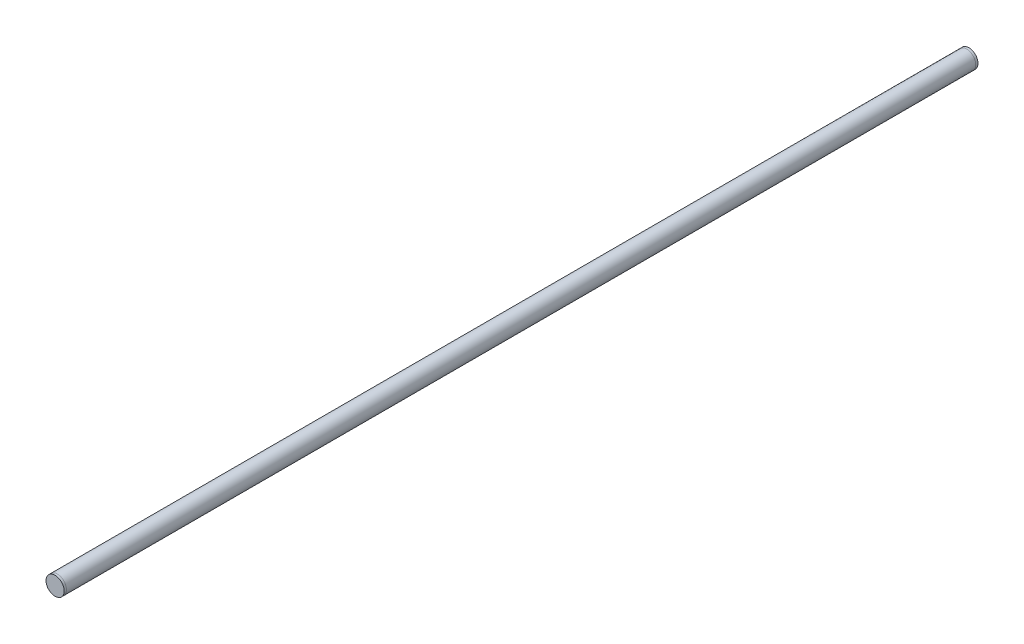
SolidWorks part; units mm, degrees
ref_plane "前视基准面" through (0, 0, 0) normal (0, 0, 1) x (1, 0, 0)
ref_plane "上视基准面" through (0, 0, 0) normal (0, 1, 0) x (1, 0, 0)
ref_plane "右视基准面" through (0, 0, 0) normal (1, 0, 0) x (0, 0, -1)
sketch "草图1" plane through (0, 0, 0) normal (0, 0, 1) x (1, 0, 0)
  circle A0 centre (0, 0) radius 4
  dimension "d" = 8
extrude "拉伸1" add sketch "草图1" along normal blind 400 separate body
cosmetic thread "装饰螺纹线1" parameters "l"=400, "r"=9
sketch "草图4" plane through (0, 0, 0) normal (0, 0, -1) x (-1, 0, 0)
  circle A0 centre (0, 0) radius 4
  circle A1 centre (0, 0) radius 4 construction
extrude "拉伸2" add sketch "草图4" along normal blind 1 separate body
sketch "草图5" plane through (0, 0, 400) normal (0, 0, 1) x (1, 0, 0)
  circle A0 centre (0, 0) radius 4
  circle A1 centre (0, 0) radius 4 construction
extrude "拉伸3" add sketch "草图5" along normal blind 1 separate body
